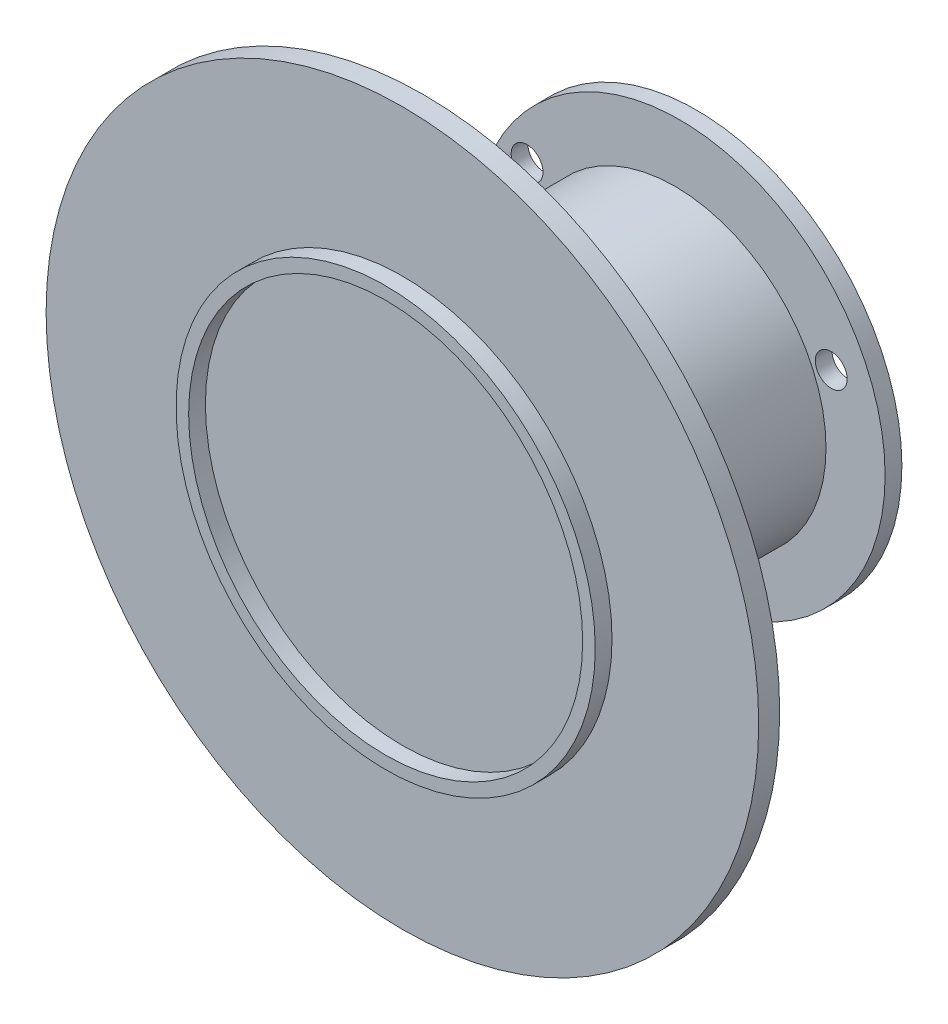
SolidWorks part; units mm, degrees
ref_plane "정면" through (0, 0, 0) normal (0, 0, 1) x (1, 0, 0)
ref_plane "윗면" through (0, 0, 0) normal (0, 1, 0) x (1, 0, 0)
ref_plane "우측면" through (0, 0, 0) normal (1, 0, 0) x (0, 0, -1)
sketch "스케치1" plane through (0, 0, 0) normal (0, 0, 1) x (1, 0, 0)
  line L0 (4.0115, 24.7508) -> (4.5002, 168.5) construction
  circle A0 centre (4.3259, 117.2199) radius 24.5
  dimension "D1" = 49
extrude "보스-돌출3" add sketch "스케치1" along normal blind 2
sketch "스케치3" plane through (0, 0, 2) normal (0, 0, 1) x (1, 0, 0)
  circle A0 centre (1.179, 95.8964) radius 1.9
  circle A1 centre (22.3957, 124.9067) radius 1.9
  circle A2 centre (-13.8821, 128.1414) radius 1.9
  dimension "D1" = 3.8
  dimension "D2" = 3.8
  dimension "D3" = 3.8
extrude "컷-돌출1" cut sketch "스케치3" against normal blind 3
sketch "스케치4" plane through (0, 0, 2) normal (0, 0, 1) x (1, 0, 0)
  circle A0 centre (3.7496, 116.5327) radius 18.0268
extrude "보스-돌출4" add sketch "스케치4" along normal blind 30
sketch "스케치5" plane through (0, 0, 32) normal (0, 0, 1) x (1, 0, 0)
  circle A0 centre (3.7496, 116.5327) radius 42.5
  dimension "D1" = 85
extrude "보스-돌출6" add sketch "스케치5" along normal blind 2.5
sketch "스케치6" plane through (0, 0, 34.5) normal (0, 0, 1) x (1, 0, 0)
  circle A1 centre (3.7496, 116.5327) radius 25
  circle A2 centre (3.7496, 116.5327) radius 23.5
  dimension "D1" = 50
  dimension "D2" = 47
extrude "보스-돌출7" add sketch "스케치6" along normal blind 2
